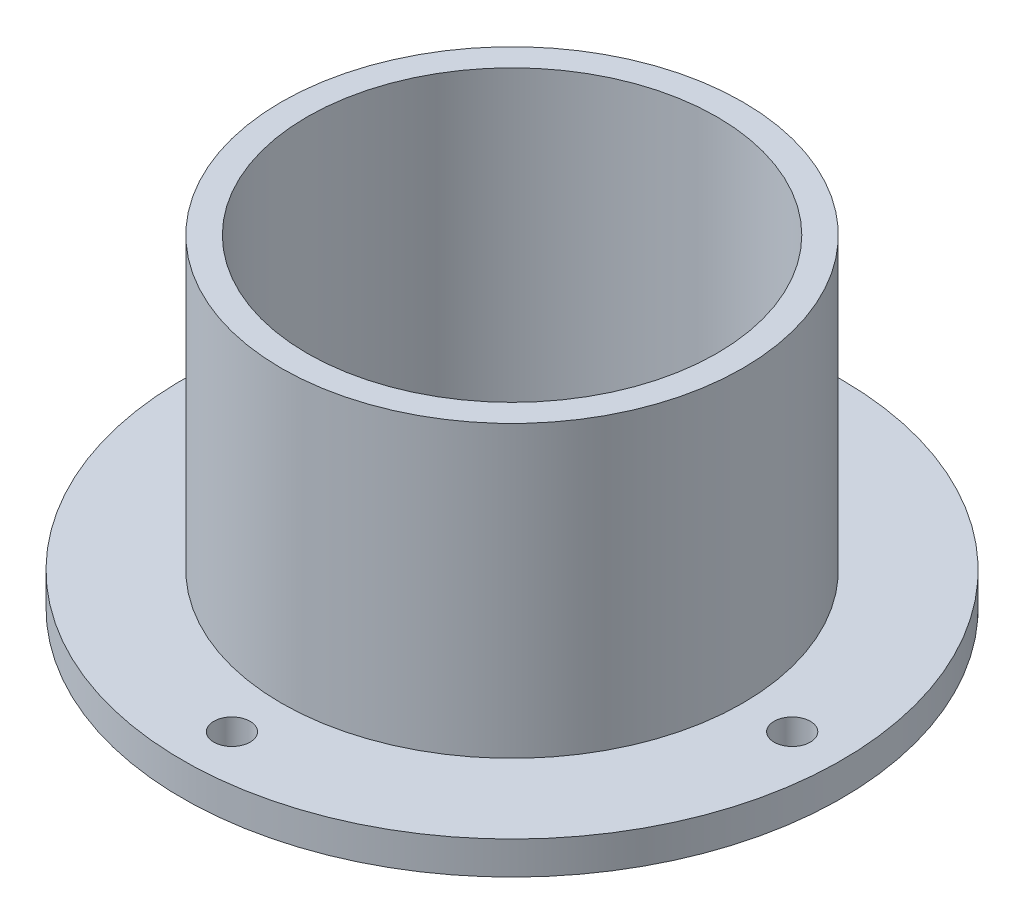
SolidWorks part; units mm, degrees
ref_plane "Front Plane" through (0, 0, 0) normal (0, 0, 1) x (1, 0, 0)
ref_plane "Top Plane" through (0, 0, 0) normal (0, 1, 0) x (1, 0, 0)
ref_plane "Right Plane" through (0, 0, 0) normal (1, 0, 0) x (0, 0, -1)
sketch "Sketch1" plane through (0, 0, 0) normal (0, 1, 0) x (1, 0, 0)
  circle A0 centre (0, 0) radius 35
  dimension "D1" = 70
extrude "Boss-Extrude1" add sketch "Sketch1" along normal blind 9
sketch "Sketch4" plane through (0, 0, 0) normal (0, -1, 0) x (1, 0, 0)
  circle A0 centre (0, 0) radius 31.0832
extrude "Cut-Extrude1" cut sketch "Sketch4" against normal blind 9
sketch "Sketch5" plane through (0, 0, 0) normal (0, -1, 0) x (1, 0, 0)
  circle A0 centre (0, 0) radius 35
  circle A1 centre (0, 0) radius 31.0832
  dimension "D1" = 70
  dimension "D2" = 62.1664
extrude "Boss-Extrude3" add sketch "Sketch5" along normal blind 40
sketch "Sketch8" plane through (0, -40, 0) normal (0, -1, 0) x (1, 0, 0)
  circle A1 centre (0, 0) radius 50
  circle A4 centre (0, 0) radius 35 construction
  dimension "D1" = 15
extrude "Boss-Extrude4" add sketch "Sketch8" against normal blind 5
sketch "Sketch10" plane through (0, -35, 0) normal (0, 1, 0) x (1, 0, 0)
  circle A0 centre (0, 42.5) radius 2.75
  circle A1 centre (0, 0) radius 42.5 construction
  circle A2 centre (0, 0) radius 50 construction
  circle A3 centre (42.5, 0) radius 2.75
  circle A4 centre (0, -42.5) radius 2.75
  circle A5 centre (-42.5, 0) radius 2.75
  point P16 (0, 0)
  dimension "D1" = 5.5
  dimension "D2" = 7.5
  dimension "D3" = 4
extrude "Cut-Extrude2" cut sketch "Sketch10" against normal blind 5
sketch "Sketch11" plane through (0, -35, 0) normal (0, 1, 0) x (1, 0, 0)
  circle A0 centre (0, 0) radius 31.0832
extrude "Cut-Extrude3" cut sketch "Sketch11" against normal blind 5
ref_plane "Plane1" through (0, 110, 0) normal (0, -1, 0) x (-1, 0, 0)
sketch "Sketch15" plane through (0, 110, 0) normal (0, -1, 0) x (-1, 0, 0)
  line L0 (0, 18.7774) -> (0, -19.5345) construction
  line L1 (16.15, 18.7774) -> (16.15, -19.5345)
  line L2 (-16.15, 18.7774) -> (-16.15, -19.5345)
  line L3 (19.15, 18.7774) -> (19.15, -19.5345)
  line L4 (-19.15, 18.7774) -> (-19.15, -19.5345)
  arc A0 (16.15, 18.7774) -> (-16.15, 18.7774) centre (0, 18.7774) ccw
  arc A1 (-16.15, -19.5345) -> (16.15, -19.5345) centre (0, -19.5345) ccw
  arc A2 (-19.15, -19.5345) -> (19.15, -19.5345) centre (0, -19.5345) ccw
  arc A3 (19.15, 18.7774) -> (-19.15, 18.7774) centre (0, 18.7774) ccw
  point P3 (0, -0.3785)
  dimension "D1" = 3
